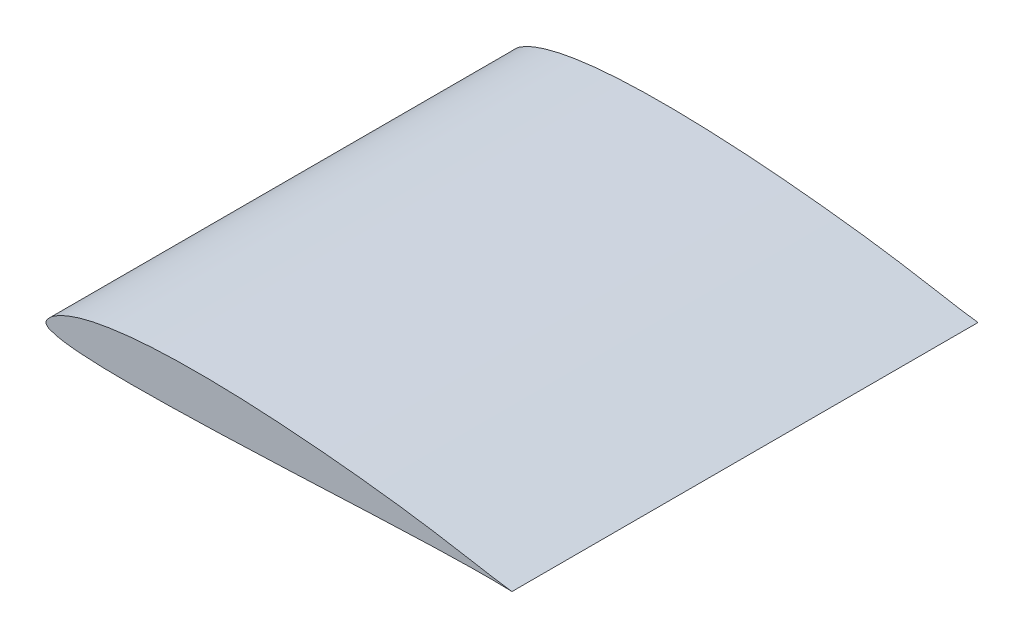
SolidWorks part; units mm, degrees
ref_plane "Front Plane" through (0, 0, 0) normal (0, 0, 1) x (1, 0, 0)
ref_plane "Top Plane" through (0, 0, 0) normal (0, 1, 0) x (1, 0, 0)
ref_plane "Right Plane" through (0, 0, 0) normal (1, 0, 0) x (0, 0, -1)
curve "Curve3"
  spline degree 3 poles (1, 0, 0) (0.9989, 0.0001, 0) (0.9946, 0.0006, 0) (0.985, 0.0019, 0) (0.9695, 0.0042, 0) (0.9485, 0.0077, 0) (0.9227, 0.0122, 0) (0.8924, 0.0175, 0) (0.8583, 0.0234, 0) (0.8207, 0.0294, 0) (0.78, 0.0354, 0) (0.7364, 0.0412, 0) (0.6906, 0.0466, 0) (0.6428, 0.0518, 0) (0.5938, 0.0565, 0) (0.5439, 0.0606, 0) (0.4938, 0.0642, 0) (0.444, 0.0669, 0) (0.3949, 0.0688, 0) (0.3472, 0.0698, 0) (0.3011, 0.0698, 0) (0.2573, 0.0688, 0) (0.216, 0.0667, 0) (0.1777, 0.0635, 0) (0.1426, 0.0592, 0) (0.1111, 0.0538, 0) (0.0832, 0.0476, 0) (0.0592, 0.0405, 0) (0.0391, 0.0328, 0) (0.0233, 0.0247, 0) (0.0112, 0.0166, 0) (0.0038, 0.0088, 0) (-0.0011, 0.0013, 0) (0.0022, -0.0066, 0) (0.0118, -0.0101, 0) (0.0249, -0.0143, 0) (0.0436, -0.0173, 0) (0.067, -0.02, 0) (0.0953, -0.0218, 0) (0.1282, -0.023, 0) (0.1653, -0.0235, 0) (0.2062, -0.0235, 0) (0.2506, -0.0229, 0) (0.2979, -0.022, 0) (0.3476, -0.0206, 0) (0.3992, -0.0189, 0) (0.4521, -0.017, 0) (0.5056, -0.0148, 0) (0.5593, -0.0125, 0) (0.6124, -0.0102, 0) (0.6645, -0.0078, 0) (0.7148, -0.0057, 0) (0.7628, -0.0037, 0) (0.8078, -0.002, 0) (0.8493, -0.0007, 0) (0.8866, 0.0002, 0) (0.9193, 0.0007, 0) (0.9468, 0.0009, 0) (0.9688, 0.0008, 0) (0.9848, 0.0006, 0) (0.9934, 0.0003, 0) (0.9967, 0.0001, 0) knots 0 0 0 0 0.001635 0.006466 0.014297 0.024884 0.037944 0.053194 0.070377 0.089257 0.109652 0.131396 0.154295 0.178097 0.202531 0.227329 0.252226 0.276966 0.301297 0.324972 0.347773 0.369494 0.389947 0.408979 0.426466 0.442307 0.456421 0.468774 0.479345 0.488156 0.495223 0.500608 0.504417 0.507344 0.511893 0.518766 0.528062 0.53975 0.553782 0.570059 0.588441 0.608748 0.63075 0.654208 0.678865 0.704451 0.730678 0.757254 0.783883 0.810266 0.836095 0.861073 0.884897 0.907258 0.927856 0.946395 0.962618 0.976286 0.987193 0.995147 1 1 1 1
sketch "Sketch2" plane through (0, 0, 0) normal (0, 0, 1) x (1, 0, 0)
  line L0 (0.9967, 0.0001) -> (1, 0)
  spline S0 degree 3 poles (-228.6487, -1986.6981) (2.8668, 2.6658) (1.7611, -0.1005) (0.985, 0.0019) (0.9695, 0.0042) (0.9485, 0.0077) (0.9227, 0.0122) (0.8924, 0.0175) (0.8583, 0.0234) (0.8207, 0.0294) (0.78, 0.0354) (0.7364, 0.0412) (0.6906, 0.0466) (0.6262, 0.0536) (0.5438, 0.061) (0.4608, 0.0663) (0.3796, 0.0694) (0.3171, 0.0702) (0.2573, 0.0688) (0.216, 0.0667) (0.1777, 0.0635) (0.1426, 0.0592) (0.1111, 0.0538) (0.0832, 0.0476) (0.0592, 0.0405) (0.0391, 0.0328) (0.0233, 0.0247) (0.0112, 0.0166) (0.0038, 0.0088) (-0.0011, 0.0013) (0.0022, -0.0066) (0.0118, -0.0101) (0.0249, -0.0143) (0.0436, -0.0173) (0.067, -0.02) (0.0953, -0.0218) (0.1282, -0.023) (0.1653, -0.0235) (0.2221, -0.0234) (0.2831, -0.0224) (0.3653, -0.0201) (0.4348, -0.0177) (0.5056, -0.0148) (0.5593, -0.0125) (0.6124, -0.0102) (0.6645, -0.0078) (0.7148, -0.0057) (0.7628, -0.0037) (0.8078, -0.002) (0.8493, -0.0007) (0.8866, 0.0002) (0.9193, 0.0007) (0.9468, 0.0009) (0.9688, 0.0008) (2.4095, -0.0215) (3.7143, -4.6952) (60.488, 1999.0865) knots -1.14555 -1.14555 -1.14555 -1.14555 0.001635 0.006466 0.014297 0.024884 0.037944 0.053194 0.070377 0.089257 0.109652 0.131396 0.154295 0.178097 0.227329 0.276966 0.301297 0.347773 0.369494 0.389947 0.408979 0.426466 0.442307 0.456421 0.468774 0.479345 0.488156 0.495223 0.500608 0.504417 0.507344 0.511893 0.518766 0.528062 0.53975 0.553782 0.570059 0.588441 0.608748 0.654208 0.678865 0.730678 0.757254 0.783883 0.810266 0.836095 0.861073 0.884897 0.907258 0.927856 0.946395 0.962618 0.976286 0.987193 0.995147 3.111308 3.111308 3.111308 3.111308 only from (1, 0) to (0.9967, 0.0001) construction
  spline S1 degree 3 poles (1, 0) (0.9989, 0.0001) (0.9946, 0.0006) (0.985, 0.0019) (0.9695, 0.0042) (0.9485, 0.0077) (0.9227, 0.0122) (0.8924, 0.0175) (0.8583, 0.0234) (0.8207, 0.0294) (0.78, 0.0354) (0.7364, 0.0412) (0.6906, 0.0466) (0.6262, 0.0536) (0.5438, 0.061) (0.4608, 0.0663) (0.3796, 0.0694) (0.3171, 0.0702) (0.2573, 0.0688) (0.216, 0.0667) (0.1777, 0.0635) (0.1426, 0.0592) (0.1111, 0.0538) (0.0832, 0.0476) (0.0592, 0.0405) (0.0391, 0.0328) (0.0233, 0.0247) (0.0112, 0.0166) (0.0038, 0.0088) (-0.0011, 0.0013) (0.0022, -0.0066) (0.0118, -0.0101) (0.0249, -0.0143) (0.0436, -0.0173) (0.067, -0.02) (0.0953, -0.0218) (0.1282, -0.023) (0.1653, -0.0235) (0.2221, -0.0234) (0.2831, -0.0224) (0.3653, -0.0201) (0.4348, -0.0177) (0.5056, -0.0148) (0.5593, -0.0125) (0.6124, -0.0102) (0.6645, -0.0078) (0.7148, -0.0057) (0.7628, -0.0037) (0.8078, -0.002) (0.8493, -0.0007) (0.8866, 0.0002) (0.9193, 0.0007) (0.9468, 0.0009) (0.9688, 0.0008) (0.9848, 0.0006) (0.9934, 0.0003) (0.9967, 0.0001) knots 0 0 0 0 0.001635 0.006466 0.014297 0.024884 0.037944 0.053194 0.070377 0.089257 0.109652 0.131396 0.154295 0.178097 0.227329 0.276966 0.301297 0.347773 0.369494 0.389947 0.408979 0.426466 0.442307 0.456421 0.468774 0.479345 0.488156 0.495223 0.500608 0.504417 0.507344 0.511893 0.518766 0.528062 0.53975 0.553782 0.570059 0.588441 0.608748 0.654208 0.678865 0.730678 0.757254 0.783883 0.810266 0.836095 0.861073 0.884897 0.907258 0.927856 0.946395 0.962618 0.976286 0.987193 0.995147 1 1 1 1
extrude "Boss-Extrude1" add sketch "Sketch2" along normal blind 1
